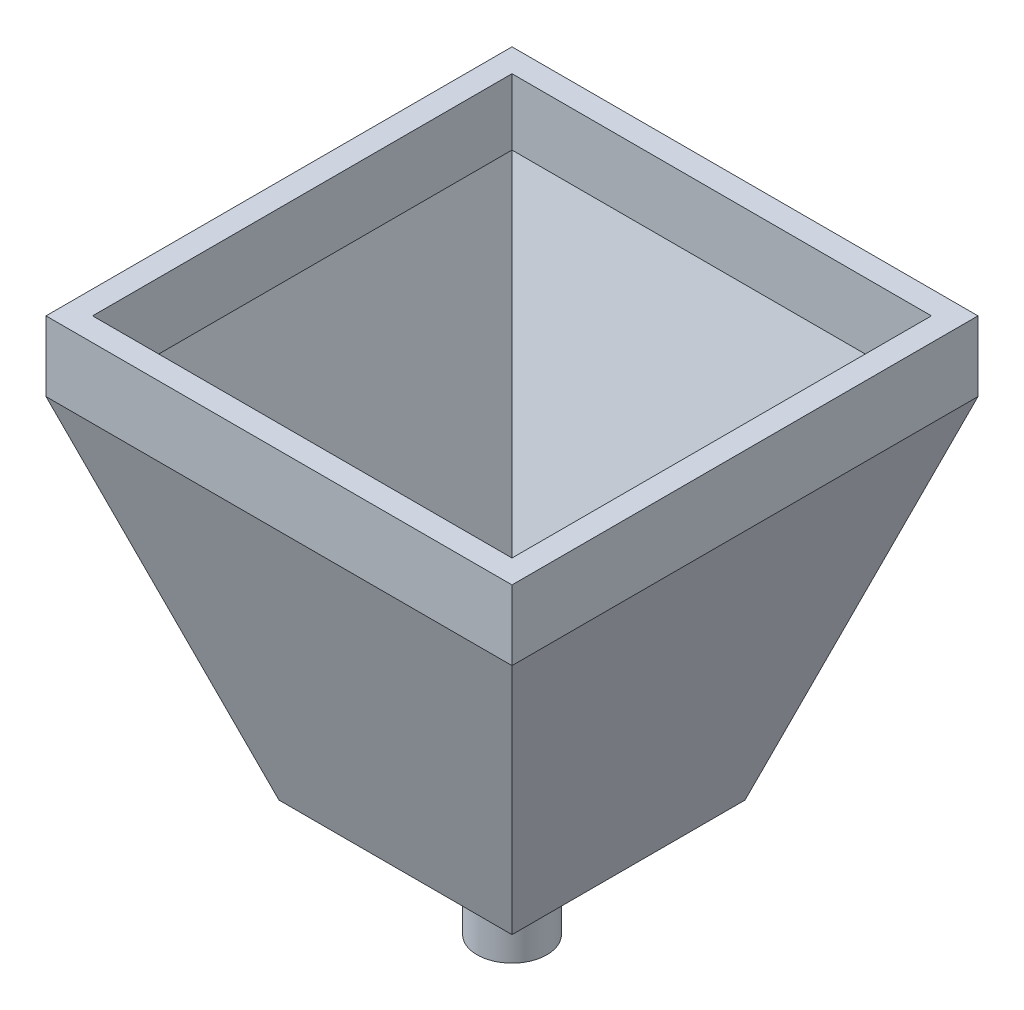
SolidWorks part; units mm, degrees
ref_plane "Alzado" through (0, 0, 0) normal (0, 0, 1) x (1, 0, 0)
ref_plane "Planta" through (0, 0, 0) normal (0, 1, 0) x (1, 0, 0)
ref_plane "Vista lateral" through (0, 0, 0) normal (1, 0, 0) x (0, 0, -1)
sketch "Croquis1" plane through (0, 0, 0) normal (0, 1, 0) x (1, 0, 0)
  line L1 (-5, -5) -> (5, -5)
  line L2 (-5, -5) -> (-5, 5)
  line L3 (-5, 5) -> (5, 5)
  line L4 (5, -5) -> (5, 5)
  line L5 (-5, -5) -> (5, 5) construction
  line L6 (-5, 5) -> (5, -5) construction
  point P0 (0, 0)
  point P6 (0, 0)
  point P7 (0, 0)
  dimension "D1" = 10
  dimension "D2" = 10
ref_plane "Plano1" through (0, 15, 0) normal (0, 1, 0) x (1, 0, 0)
sketch "Croquis2" plane through (0, 15, 0) normal (0, 1, 0) x (1, 0, 0)
  line L1 (-10, -10) -> (10, -10)
  line L2 (-10, -10) -> (-10, 10)
  line L3 (-10, 10) -> (10, 10)
  line L4 (10, -10) -> (10, 10)
  line L5 (-10, -10) -> (10, 10) construction
  line L6 (-10, 10) -> (10, -10) construction
  point P0 (0, 0)
  dimension "D1" = 20
  dimension "D2" = 20
loft "Recubrir1" add profiles "Croquis2", "Croquis1"
sketch "Croquis3" plane through (0, 15, 0) normal (0, 1, 0) x (1, 0, 0)
  line L1 (10, -10) -> (-10, -10)
  line L2 (10, -10) -> (10, 10)
  line L3 (10, 10) -> (-10, 10)
  line L4 (-10, -10) -> (-10, 10)
  line L5 (10, -10) -> (-10, 10) construction
  line L6 (10, 10) -> (-10, -10) construction
  point P0 (0, 0)
extrude "Saliente-Extruir1" add sketch "Croquis3" along normal blind 3
shell "Vaciado2" thickness 1
sketch "Croquis4" plane through (0, 0, 0) normal (0, -1, 0) x (-1, 0, 0)
  circle A0 centre (0, 0) radius 1.5
  dimension "D1" = 3
extrude "Cortar-Extruir1" cut sketch "Croquis4" against normal blind 3
sketch "Croquis5" plane through (0, 0, 0) normal (0, -1, 0) x (-1, 0, 0)
  circle A0 centre (0, 0) radius 1.5
extrude "Saliente-Extruir2" add sketch "Croquis5" along normal blind 5 separate body
sketch "Croquis6" plane through (0, -5, 0) normal (0, -1, 0) x (-1, 0, 0)
  circle A0 centre (0, 0) radius 1.3559
extrude "Cortar-Extruir2" cut sketch "Croquis6" against normal blind 15
sketch "Croquis7" plane through (0, 0, 0) normal (1, 0, 0) x (0, 0, -1)
  circle A0 centre (0, -2.4392) radius 1
  point P2 (0, -2.4392)
  dimension "D1" = 2
extrude "Saliente-Extruir4" add sketch "Croquis7" along normal blind 1.5
ref_plane "Plano4" through (1.5, 0, 0) normal (1, 0, 0) x (0, 0, -1)
sketch "Croquis10" plane through (0, 0, 0) normal (0, -1, 0) x (-1, 0, 0)
  circle A0 centre (0, 0) radius 1.4064
extrude "Cortar-Extruir3" cut sketch "Croquis10" against normal blind 1.5 and the other way blind 31.5
ref_plane "Plano5" through (0, 0, -110) normal (0, 0, -1) x (-1, 0, 0)
